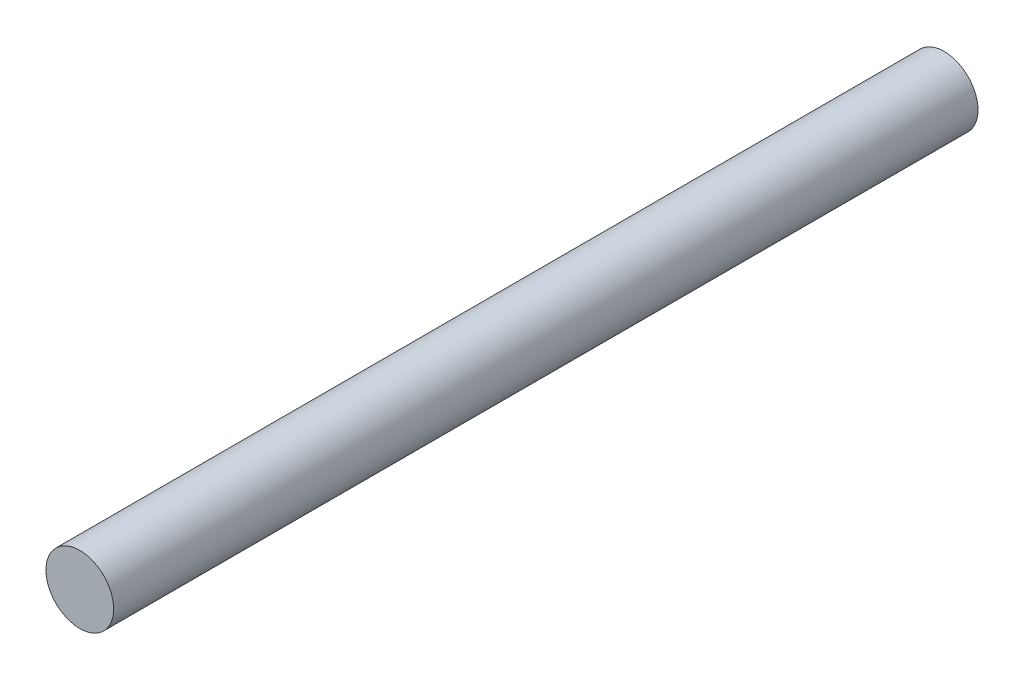
SolidWorks part; units mm, degrees
ref_plane "Front Plane" through (0, 0, 0) normal (0, 0, 1) x (1, 0, 0)
ref_plane "Top Plane" through (0, 0, 0) normal (0, 1, 0) x (1, 0, 0)
ref_plane "Right Plane" through (0, 0, 0) normal (1, 0, 0) x (0, 0, -1)
sketch "Sketch1" plane through (0, 0, 0) normal (0, 0, 1) x (1, 0, 0)
  circle A0 centre (0, 0) radius 49.95
  dimension "D1" = 99.9
extrude "Boss-Extrude1" add sketch "Sketch1" along normal blind 1275
